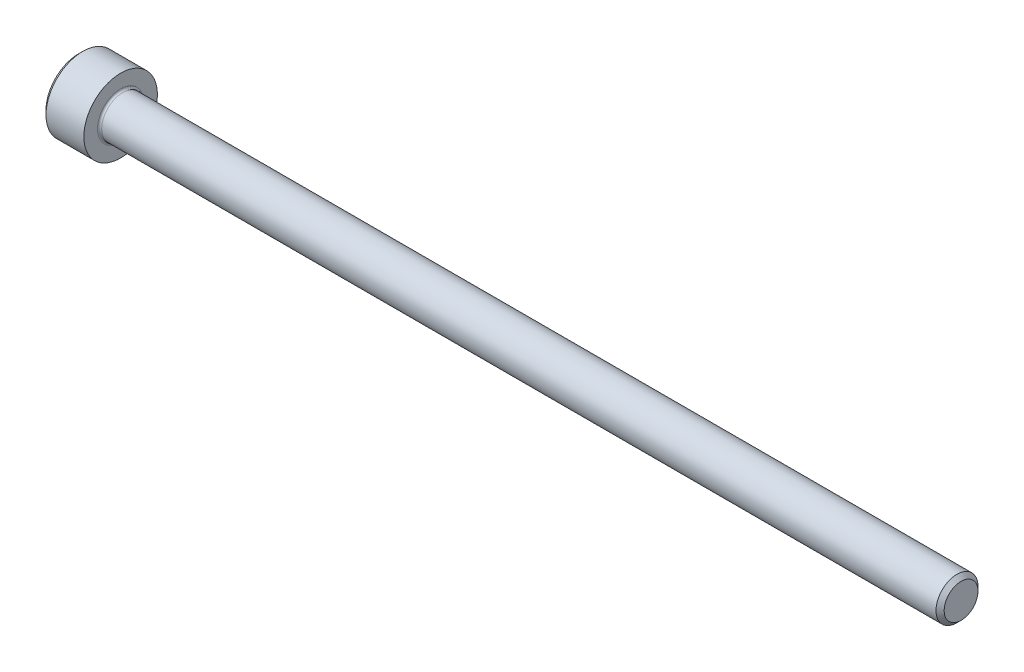
SolidWorks part; units mm, degrees
revolve "Base-Revolve" add sketch "BodySke"
sketch "BodySke" plane through (0, 0, 0) normal (0, 0, 1) x (1, 0, 0)
  line L0 (0, 0) -> (0, 3.1)
  line L1 (0.4, 3.5) -> (4, 3.5)
  line L2 (4, 3.5) -> (4, 2)
  line L3 (4, 2) -> (83.61, 2)
  line L4 (84, 1.61) -> (84, 0)
  line L5 (84, 0) -> (0, 0)
  line L6 (-31.75, 0) -> (127, 0) construction
  line L7 (0, 3.1) -> (0.4, 3.5)
  line L8 (84, 1.61) -> (83.61, 2)
  line L9 (0, -3.1) -> (0.4, -3.5) construction
  line L10 (84, -1.61) -> (83.61, -2) construction
  line L11 (4.7, 0.783) -> (4.7, -5.567) construction
  line L12 (64, 0.783) -> (64, -5.567) construction
  line L13 (34, 0.783) -> (34, -5.567) construction
  dimension "Diameter" = 4
  dimension "Head_ht" = 4
  dimension "Length" = 80
  dimension "Body_ch_ang" = 45
  dimension "Head_dia" = 7
  dimension "Head_ch_ang" = 45
  dimension "Minor_dia" = 3.22
  dimension "Advance" = 0.7
  dimension "Thread_nom" = 20
  dimension "Thread_length" = 50
  dimension "Head_ch_ht" = 0.4
cosmetic thread "ThreadCosmetic" [suppressed]
fillet "Fillet1" radius 0.2 1 edges at (4, 0, 2)
ref_plane "Plane1" through (0, 0, 0) normal (0, 0, 1) x (1, 0, 0)
ref_plane "Plane2" through (0, 0, 0) normal (0, 1, 0) x (1, 0, 0)
ref_plane "Plane3" through (0, 0, 0) normal (1, 0, 0) x (0, 0, -1)
other "Configuration Table"
sketch "Sketch2" plane through (0, 0, 0) normal (0, 0, 1) x (1, 0, 0)
  line L0 (0, 1.5355) -> (2, 1.5355)
  line L1 (2, 1.5355) -> (2.8865, 0)
  line L2 (-31.75, 0) -> (127, 0) construction
  line L3 (2.8865, 0) -> (0, 0)
  line L4 (0, 0) -> (0, 1.5355)
  line L5 (0, 3.1) -> (0, -3.1) construction
  line L6 (0, 0) -> (47.625, 0) construction
  line L7 (4, -3.5) -> (4, 3.5) construction
  dimension "D1" = 1.5355
  dimension "D2" = 60
revolve "Hex-PreBroach" cut sketch "Sketch2" angle 360 about L6
sketch "Sketch3" plane through (0, 0, 0) normal (-1, 0, 0) x (0, 0.5, 0.866)
  line L0 (0.8865, 1.5355) -> (-0.8865, 1.5355)
  line L1 (-0.8865, 1.5355) -> (-1.773, 0)
  line L2 (0.8865, 1.5355) -> (1.773, 0)
  line L3 (0.8865, -1.5355) -> (1.773, 0)
  line L4 (0.8865, -1.5355) -> (-0.8865, -1.5355)
  line L5 (-0.8865, -1.5355) -> (-1.773, 0)
  dimension "D1" = 1.5355
  dimension "D2" = 1.5355
  dimension "Hex_size" = 3.071
extrude "Hex" cut sketch "Sketch3" against normal blind 2
sketch "Sketch4" plane through (0, 0, 0) normal (-1, 0, 0) x (0, 0, 1)
  line L0 (0, 0) -> (1.7399, 0)
  line L1 (0, 0) -> (6.1484, 3.5498) construction
  line L2 (0, 0) -> (0.8699, 1.5068)
  line L3 (1.4457, 0.3947) -> (1.6607, 0.5189)
  line L4 (1.0647, 1.0546) -> (1.2797, 1.1788)
  arc A0 (1.4457, 0.3947) -> (1.0647, 1.0546) centre (0, 0) ccw
  arc A1 (1.7399, 0) -> (1.6607, 0.5189) centre (0, 0) ccw
  arc A2 (0.8699, 1.5068) -> (1.2797, 1.1788) centre (0, 0) cw
  dimension "D1" = 30
  dimension "D2" = 60
  dimension "Spline_p_dim" = 0.762
  dimension "D3" = 0.381
extrude "Spline" [suppressed] cut sketch "Sketch4" against normal blind 2
pattern_circular "CirPattern1" [suppressed] count 6 every 60
sketch "Sketch5" plane through (0, 0, 0) normal (0, 0, 1) x (1, 0, 0)
  line L0 (-31.75, 0) -> (127, 0) construction
  line L2 (0, 3.1) -> (0, -3.1) construction
  circle A0 centre (1.6, 0) radius 0.675
  dimension "Drilled_hole_dia" = 1.35
  dimension "Drilled_hole_loc" = 1.6
extrude "Hole" [suppressed] cut sketch "Sketch5" against normal through all and the other way through all
pattern_circular "Drilled-4" [suppressed] count 2 every 60
pattern_circular "Drilled-6" [suppressed] count 3 every 60
sketch "ThdSchSke" plane through (0, 0, 0) normal (0, 0, 1) x (1, 0, 0)
  line L0 (64, -1.61) -> (63.7269, -2)
  line L1 (64, -1.61) -> (64.2731, -2)
  line L2 (64.2731, -2) -> (64.2731, -2.5)
  line L3 (-3.175, 0) -> (5.1513, 0) construction
  line L5 (64.2731, -2.5) -> (63.7269, -2.5)
  line L6 (63.7269, -2.5) -> (63.7269, -2)
  line L7 (0, 3.1) -> (0, -3.1) construction
  dimension "Thread_minor" = 3.22
  dimension "Diameter" = 4
  dimension "Start" = 64
revolve "ThreadSchematic" [suppressed] cut sketch "ThdSchSke" angle 360 about L3
pattern_linear "ThdSchPat" [suppressed]
equation "\"D2@Sketch3\" = \"Hex_size@Sketch3\" / 2"
equation "\"D1@Sketch3\" = \"Hex_size@Sketch3\" / 2"
equation "\"D1@Sketch2\" = \"Hex_size@Sketch3\" / 2"
equation "\"D3@Sketch4\" = \"Spline_p_dim@Sketch4\" / 2"
equation "\"Thread_minor@ThreadCosmetic\"  =  \"Minor_dia@BodySke\""
equation "\"D2@CirPattern1\" = 360 / \"Num_teeth@CirPattern1\""
equation "\"Wall_thickness@Sketch2\" = \"Head_ht@BodySke\" - \"Key_eng@Hex\""
equation "\"Thread_length@ThreadCosmetic\" = ((sgn( (\"Length@BodySke\" - \"Advance@BodySke\" ) - \"Thread_nom@BodySke\" )-1)*( (\"Length@BodySke\" - \"Advance@BodySke\" ) - \"Thread_nom@BodySke\" ))/-2+ \"Thread_nom@BodySke\""
equation "\"Thread_minor@ThdSchSke\" = \"Minor_dia@BodySke\""
equation "\"Diameter@ThdSchSke\" = \"Diameter@BodySke\""
equation "\"Overcut@ThdSchSke\" = \"Diameter@BodySke\" * 1.25"
equation "\"Start@ThdSchSke\" = \"Head_ht@BodySke\" + \"Length@BodySke\" - \"Thread_length@ThreadCosmetic\"  '---Non-countersunk---"
equation "\"Num_threads@ThdSchPat\" = int( \"Thread_length@ThreadCosmetic\" / \"Advance@BodySke\" + 0.999 )  + 1"
equation "\"Advance@ThdSchPat\" = \"Thread_length@ThreadCosmetic\" /  (\"Num_threads@ThdSchPat\" - 1) 'relax it"
equation "\"Num_threads@ThdSchPat\" = \"Num_threads@ThdSchPat\" - sgn( \"Num_threads@ThdSchPat\" - 1) '---chamfered tips only---"
